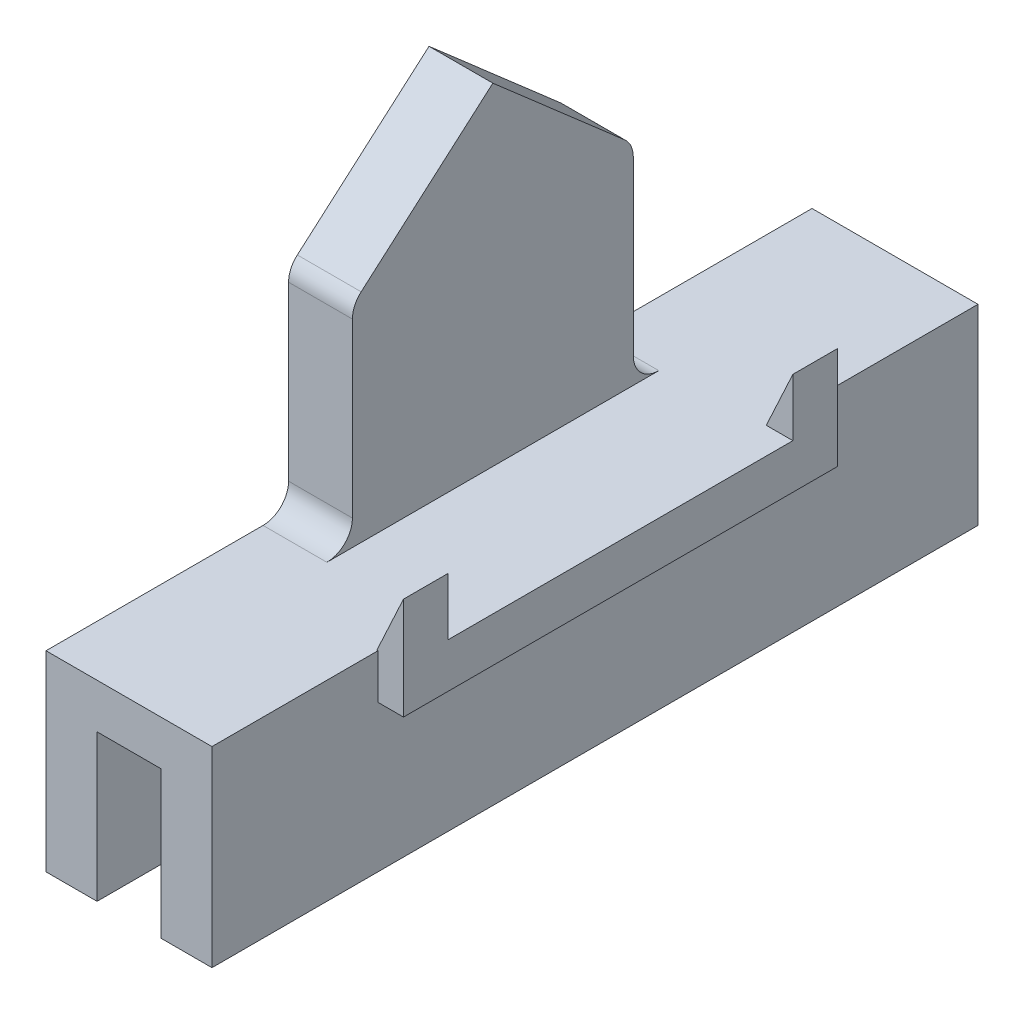
SolidWorks part; units mm, degrees
ref_plane "前视基准面" through (0, 0, 0) normal (0, 0, 1) x (1, 0, 0)
ref_plane "上视基准面" through (0, 0, 0) normal (0, 1, 0) x (1, 0, 0)
ref_plane "右视基准面" through (0, 0, 0) normal (1, 0, 0) x (0, 0, -1)
sketch "草图1" plane through (0, 0, 0) normal (0, 0, 1) x (1, 0, 0)
  line L1 (-6.5, -7.5) -> (-2.5, -7.5)
  line L2 (-6.5, -7.5) -> (-6.5, 7.5)
  line L3 (-6.5, 7.5) -> (6.5, 7.5)
  line L4 (6.5, -7.5) -> (6.5, 7.5)
  line L5 (-6.5, -7.5) -> (6.5, 7.5) construction
  line L6 (-6.5, 7.5) -> (6.5, -7.5) construction
  line L7 (-2.5, -7.5) -> (-2.5, 4)
  line L8 (2.5, -7.5) -> (2.5, 4)
  line L9 (-2.5, 4) -> (2.5, 4)
  line L10 (2.5, -7.5) -> (6.5, -7.5)
  point P0 (0, 0)
  dimension "D1" = 15
  dimension "D2" = 13
  dimension "D3" = 5
  dimension "D4" = 4
  dimension "D5" = 3.5
extrude "凸台-拉伸1" add sketch "草图1" along normal blind 60
sketch "草图2" plane through (-6.5, 0, 0) normal (-1, 0, 0) x (0, 0, 1)
  line L6 (19, 7.5) -> (41, 7.5)
  line L7 (19, 7.5) -> (19, 23.9069)
  line L8 (41, 7.5) -> (41, 23.9069)
  line L10 (60, 7.5) -> (0, 7.5) construction
  line L11 (0, 7.5) -> (0, -7.5) construction
  line L12 (19, 23.9069) -> (30, 33.5)
  line L13 (30, 33.5) -> (41, 23.9069)
  line L14 (60, -7.5) -> (0, -7.5) construction
  dimension "D1" = 22
  dimension "D2" = 19
  dimension "D3" = 41
extrude "凸台-拉伸2" add sketch "草图2" against normal blind 5
sketch "草图3" plane through (6.5, 0, 0) normal (1, 0, 0) x (0, 0, -1)
  line L0 (-47, 7.5) -> (-47, 4)
  line L1 (-60, 7.5) -> (0, 7.5) construction
  line L2 (-47, 4) -> (-13, 4)
  line L3 (-13, 4) -> (-13, 7.5)
  line L4 (-13, 7.5) -> (-47, 7.5)
  line L5 (-60, -7.5) -> (-60, 7.5) construction
  dimension "D1" = 34
  dimension "D2" = 13
  dimension "D3" = 3.5
extrude "凸台-拉伸3" add sketch "草图3" along normal blind 2
sketch "草图4" plane through (0, 0, 47) normal (0, 0, 1) x (1, 0, 0)
  line L0 (8.5, 4) -> (8.5, 12)
  line L1 (8.5, 12) -> (4.7956, 4)
  line L2 (4.7956, 4) -> (8.5, 4)
  dimension "D1" = 8
extrude "凸台-拉伸4" add sketch "草图4" against normal blind 3.5
ref_plane "基准面1" through (0, 0, 30) normal (0, 0, 1) x (1, 0, 0)
mirror "镜向1" about plane through (0, 0, 30) normal (0, 0, 1) of "凸台-拉伸4"
fillet "圆角1" radius 2 1 edges at (-4, 7.5, 41)
fillet "圆角2" radius 2 1 edges at (-4, 7.5, 19)
fillet "圆角3" radius 2 1 edges at (-4, 23.9069, 19)
fillet "圆角4" radius 2 1 edges at (-4, 23.9069, 41)
